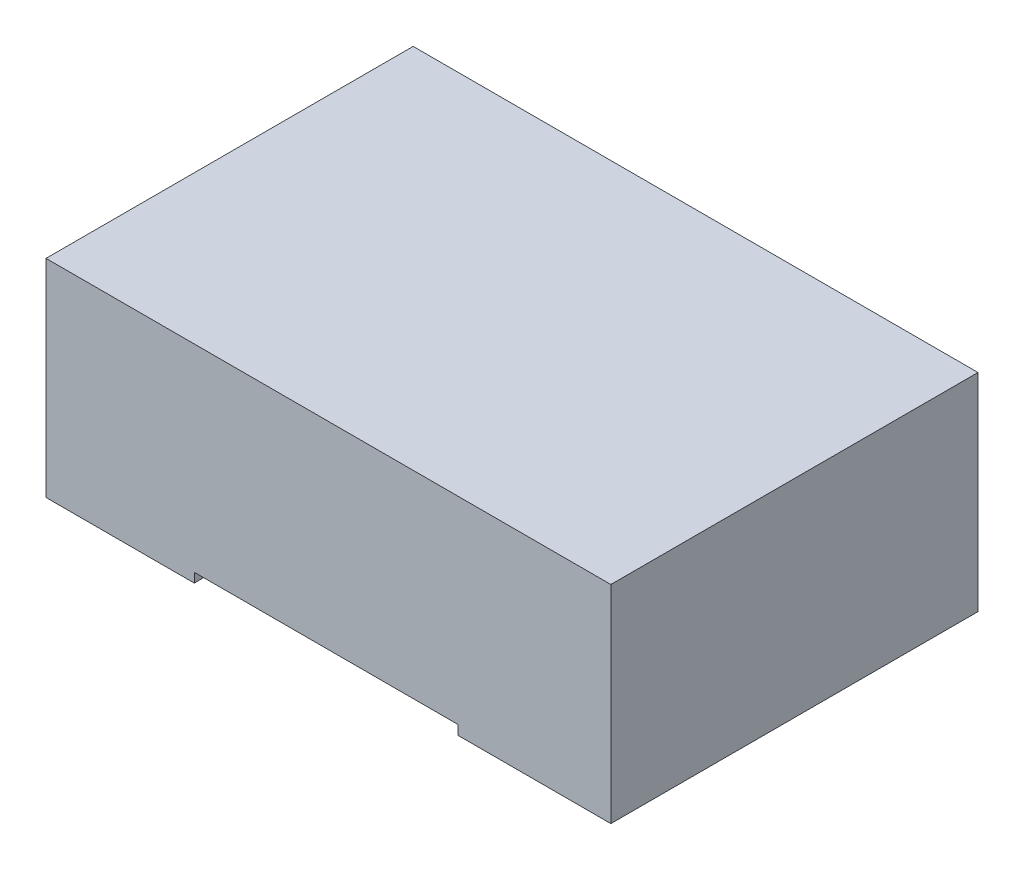
SolidWorks part; units mm, degrees
ref_plane "Front Plane" through (0, 0, 0) normal (0, 0, 1) x (1, 0, 0)
ref_plane "Top Plane" through (0, 0, 0) normal (0, 1, 0) x (1, 0, 0)
ref_plane "Right Plane" through (0, 0, 0) normal (1, 0, 0) x (0, 0, -1)
sketch "Sketch1" plane through (0, 0, 0) normal (0, 1, 0) x (1, 0, 0)
  line L1 (-60, 45) -> (0, 45)
  line L2 (-60, 45) -> (-60, 0)
  line L3 (-60, 0) -> (0, 0)
  line L4 (0, 45) -> (0, 0)
  dimension "D1" = 60
  dimension "D2" = 45
extrude "Boss-Extrude1" add sketch "Sketch1" along normal blind 30
sketch "Sketch2" plane through (0, 0, 0) normal (0, -1, 0) x (-1, 0, 0)
  line L0 (60, 45) -> (60, 0) construction
  line L1 (50.75, 13) -> (44.25, 13)
  line L2 (50.75, 13) -> (50.75, 29)
  line L3 (50.75, 29) -> (44.25, 29)
  line L4 (44.25, 13) -> (44.25, 29)
  line L5 (16.25, 13) -> (9.75, 13)
  line L6 (16.25, 13) -> (16.25, 29)
  line L7 (16.25, 29) -> (9.75, 29)
  line L8 (9.75, 13) -> (9.75, 29)
  line L10 (0, 0) -> (0, 45) construction
  line L12 (0, 45) -> (60, 45) construction
  dimension "D1" = 16
  dimension "D2" = 6.5
  dimension "D3" = 9.25
  dimension "D4" = 6.5
  dimension "D5" = 16
  dimension "D6" = 9.75
  dimension "D7" = 16
extrude "Cut-Extrude1" cut sketch "Sketch2" against normal blind 20
chamfer "Chamfer1" distance 5 angle 5 4 edges at (-16.25, 20, -21) (-9.75, 20, -21) (-50.75, 20, -21) (-44.25, 20, -21)
chamfer "Chamfer2" distance 5 angle 50 4 edges at (-47.5, 20, -29) (-13, 20, -29) (-13, 20, -13) (-47.5, 20, -13)
sketch "Sketch4" plane through (0, 0, -45) normal (0, 0, -1) x (-1, 0, 0)
  line L0 (11.5, 0) -> (28.3, 0)
  line L1 (0, 0) -> (60, 0) construction
  arc A0 (28.3, 0) -> (42.6119, 6.1301) centre (38.1836, -3.3031) cw
  arc A1 (42.6119, 6.1301) -> (46.2306, 12.0745) centre (44.0992, 9.2984) ccw
  arc A2 (46.2306, 12.0745) -> (11.5, 0) centre (32.8331, -5.3756) ccw
  dimension "D3" = 3.5
  dimension "D4" = 10.4209
  dimension "D7" = 22
  dimension "D1" = 16.8
  dimension "D2" = 11.5
  dimension "D5" = 3.3031
  dimension "D6" = 9.2984
extrude "Cut-Extrude2" cut sketch "Sketch4" against normal blind 10
chamfer "Chamfer3" distance 3 distance2 1.5 8 edges at (-13, 0, -13) (-9.75, 0, -21) (-13, 0, -29) (-16.25, 0, -21) (-47.5, 0, -29) (-44.25, 0, -21) (-47.5, 0, -13) (-50.75, 0, -21)
sketch "Sketch5" plane through (-60, 0, 0) normal (-1, 0, 0) x (0, 0, 1)
  line L0 (0, 30) -> (0, 0) construction
  line L1 (-45, 30) -> (0, 30)
  line L2 (-45, 30) -> (-45, 22)
  line L4 (0, 30) -> (0, 0)
  line L5 (-45, 22) -> (-6, 22)
  line L6 (-6, 22) -> (-6, 0)
  line L7 (-45, 0) -> (0, 0) construction
  line L8 (-6, 0) -> (0, 0)
  dimension "D1" = 8
  dimension "D2" = 6
extrude "Cut-Extrude3" cut sketch "Sketch5" against normal up to next
sketch "Sketch6" plane through (0, 0, 0) normal (0, -1, 0) x (-1, 0, 0)
  line L0 (0, 6) -> (60, 6) construction
  line L1 (44.25, 37) -> (16.25, 37)
  line L2 (44.25, 37) -> (44.25, 6)
  line L3 (44.25, 6) -> (16.25, 6)
  line L4 (16.25, 37) -> (16.25, 6)
  line L5 (44.25, 29) -> (44.25, 13) construction
  line L7 (16.25, 13) -> (16.25, 29) construction
  dimension "D1" = 31
extrude "Cut-Extrude4" cut sketch "Sketch6" against normal blind 1
